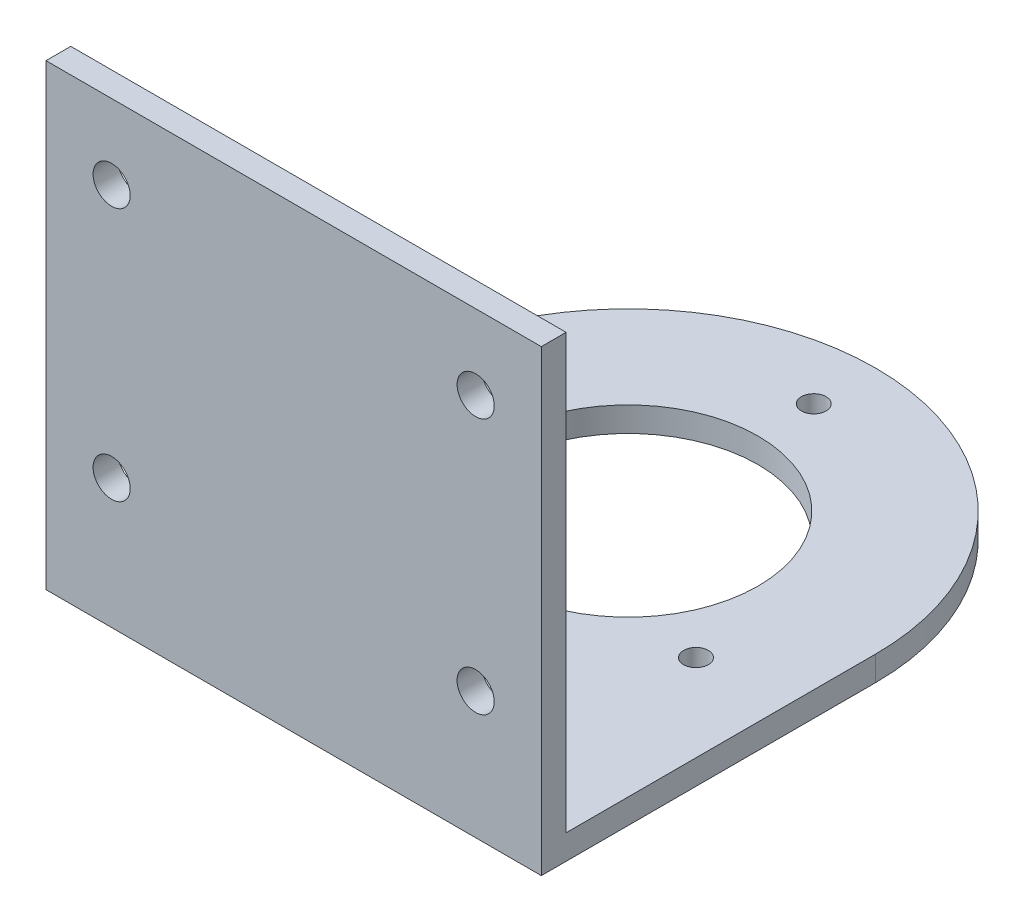
SolidWorks part; units mm, degrees
ref_plane "Front Plane" through (0, 0, 0) normal (0, 0, 1) x (1, 0, 0)
ref_plane "Top Plane" through (0, 0, 0) normal (0, 1, 0) x (1, 0, 0)
ref_plane "Right Plane" through (0, 0, 0) normal (1, 0, 0) x (0, 0, -1)
sketch "Sketch1" plane through (0, 0, 0) normal (0, 1, 0) x (1, 0, 0)
  line L2 (-18.2292, 5.4375) -> (-18.2292, -21.5625)
  line L3 (-18.2292, -21.5625) -> (21.7708, -21.5625)
  line L4 (21.7708, 5.4375) -> (21.7708, -21.5625)
  arc A0 (21.7708, 5.4375) -> (-18.2292, 5.4375) centre (1.7708, 5.4375) ccw
  circle A1 centre (1.7708, 5.4375) radius 10.5
  dimension "D3" = 21
  dimension "D1" = 27
  dimension "D2" = 40
extrude "Boss-Extrude2" add sketch "Sketch1" along normal blind 2
sketch "Sketch2" plane through (0, 2, 0) normal (0, 1, 0) x (1, 0, 0)
  line L0 (21.7708, -21.5625) -> (21.7708, 5.4375) construction
  line L1 (-18.2292, -21.5625) -> (21.7708, -21.5625)
  line L2 (-18.2292, -21.5625) -> (-18.2292, -19.5625)
  line L3 (-18.2292, -19.5625) -> (21.7708, -19.5625)
  line L4 (21.7708, -21.5625) -> (21.7708, -19.5625)
  dimension "D1" = 2
extrude "Boss-Extrude3" add sketch "Sketch2" along normal blind 35
sketch "Sketch4" plane through (0, 2, 0) normal (0, 1, 0) x (1, 0, 0)
  line L0 (1.7708, 5.4375) -> (1.7708, 26.403)
  circle A0 centre (1.7708, 20.4375) radius 1
  dimension "D1" = 2
  dimension "D2" = 15
extrude "Cut-Extrude1" cut sketch "Sketch4" against normal blind 35 contours L0 A0 | L0 A0
pattern_circular "CirPattern1" count 3 over 360 about axis through (1.7708, 0, -5.4375) along (0, 1, 0) of "Cut-Extrude1"
sketch "Sketch5" plane through (0, 0, 19.5625) normal (0, 0, -1) x (-1, 0, 0)
  line L0 (-1.7708, 37) -> (-1.7708, -1.3606)
  line L1 (-21.7708, 37) -> (18.2292, 37) construction
  line L2 (-21.7708, 37) -> (-21.7708, 2) construction
  circle A0 centre (-16.4708, 30.9525) radius 1.5
  circle A1 centre (-16.4669, 10.2624) radius 1.5
  dimension "D1" = 3
  dimension "D2" = 3
  dimension "D3" = 5.3
extrude "Cut-Extrude2" cut sketch "Sketch5" against normal blind 35 contours A1 | A0
sketch "Sketch6" plane through (0, 0, 19.5625) normal (0, 0, -1) x (-1, 0, 0)
  line L0 (18.2292, 37) -> (18.2292, 2) construction
  circle A0 centre (12.9292, 30.9642) radius 1.5
  circle A1 centre (12.9292, 10.4709) radius 1.5
  dimension "D1" = 3
  dimension "D2" = 3
  dimension "D3" = 5.3
  dimension "D4" = 5.3
extrude "Cut-Extrude3" cut sketch "Sketch6" against normal blind 35
